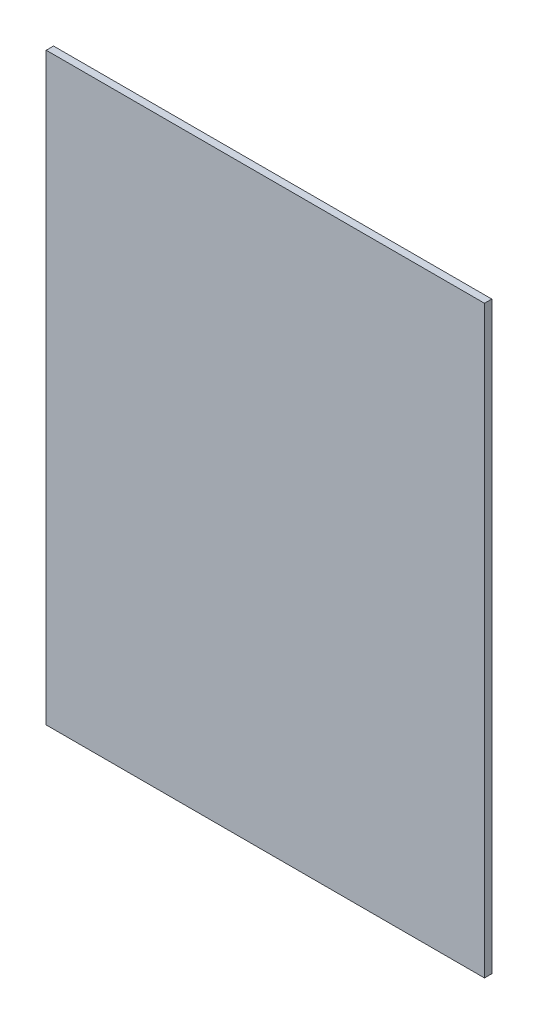
SolidWorks part; units mm, degrees
ref_plane "Front Plane" through (0, 0, 0) normal (0, 0, 1) x (1, 0, 0)
ref_plane "Top Plane" through (0, 0, 0) normal (0, 1, 0) x (1, 0, 0)
ref_plane "Right Plane" through (0, 0, 0) normal (1, 0, 0) x (0, 0, -1)
sketch "Sketch1" plane through (0, 0, 0) normal (0, 0, 1) x (1, 0, 0)
  line L1 (0, 0) -> (304.8, 0)
  line L2 (0, 0) -> (0, 406.4)
  line L3 (0, 406.4) -> (304.8, 406.4)
  line L4 (304.8, 0) -> (304.8, 406.4)
  dimension "D1" = 406.4
  dimension "D2" = 304.8
extrude "Boss-Extrude1" add sketch "Sketch1" along normal blind 5.08
